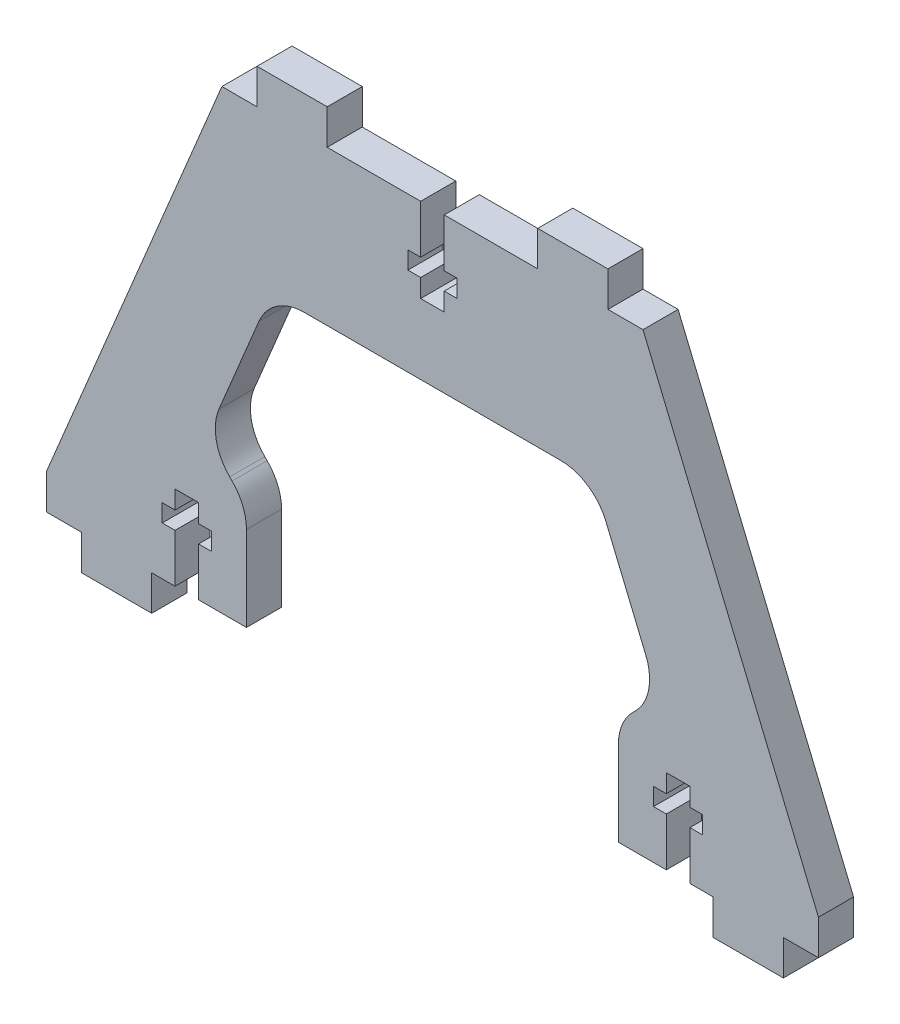
SolidWorks part; units mm, degrees
ref_plane "Front Plane" through (0, 0, 0) normal (0, 0, 1) x (1, 0, 0)
ref_plane "Top Plane" through (0, 0, 0) normal (0, 1, 0) x (1, 0, 0)
ref_plane "Right Plane" through (0, 0, 0) normal (1, 0, 0) x (0, 0, -1)
sketch "Sketch1" plane through (0, 0, 0) normal (0, 0, 1) x (1, 0, 0)
  line L1 (-69.85, 41.275) -> (69.85, 41.275)
  line L2 (-69.85, 41.275) -> (-69.85, -41.275)
  line L3 (-69.85, -41.275) -> (69.85, -41.275)
  line L4 (69.85, 41.275) -> (69.85, -41.275)
  line L5 (-69.85, 41.275) -> (69.85, -41.275) construction
  line L6 (-69.85, -41.275) -> (69.85, 41.275) construction
  point P0 (0, 0)
  dimension "D1" = 82.55
  dimension "D2" = 139.7
extrude "Boss-Extrude1" add sketch "Sketch1" along normal blind 6.35
sketch "Sketch2" plane through (0, 0, 0) normal (0, 0, -1) x (-1, 0, 0)
  line L0 (69.85, -41.275) -> (-69.85, -41.275) construction
  line L1 (-63.5, -41.275) -> (-50.8, -41.275)
  line L2 (-63.5, -41.275) -> (-63.5, -47.625)
  line L3 (-63.5, -47.625) -> (-50.8, -47.625)
  line L4 (-50.8, -41.275) -> (-50.8, -47.625)
  line L5 (-69.85, -41.275) -> (-69.85, 41.275) construction
  line L6 (-69.85, 41.275) -> (69.85, 41.275) construction
  line L7 (-31.75, 41.275) -> (-19.05, 41.275)
  line L8 (-31.75, 41.275) -> (-31.75, 47.625)
  line L9 (-31.75, 47.625) -> (-19.05, 47.625)
  line L10 (-19.05, 41.275) -> (-19.05, 47.625)
  dimension "D1" = 6.35
  dimension "D2" = 12.7
  dimension "D3" = 6.35
  dimension "D4" = 6.35
  dimension "D5" = 12.7
  dimension "D6" = 38.1
extrude "Boss-Extrude2" add sketch "Sketch2" against normal blind 6.35
sketch "Sketch3" plane through (0, 0, 0) normal (0, 0, -1) x (-1, 0, 0)
  line L1 (-46.5836, -41.275) -> (-46.5836, -32.512)
  line L2 (69.85, -41.275) -> (-50.8, -41.275) construction
  line L3 (-46.5836, -32.512) -> (-48.895, -32.512)
  line L4 (-48.895, -32.512) -> (-48.895, -29.337)
  line L5 (-48.895, -29.337) -> (-46.5836, -29.337)
  line L6 (-46.5836, -29.337) -> (-46.5836, -26.035)
  line L7 (-46.5836, -26.035) -> (-42.3164, -26.035)
  line L8 (-44.45, -26.035) -> (-44.45, -41.275) construction
  line L9 (-42.3164, -41.275) -> (-46.5836, -41.275)
  line L10 (-63.5, -47.625) -> (-50.8, -47.625) construction
  line L11 (-42.3164, -29.337) -> (-42.3164, -26.035)
  line L12 (-40.005, -29.337) -> (-42.3164, -29.337)
  line L13 (-40.005, -32.512) -> (-40.005, -29.337)
  line L14 (-42.3164, -32.512) -> (-40.005, -32.512)
  line L15 (-42.3164, -41.275) -> (-42.3164, -32.512)
  line L16 (-50.8, -47.625) -> (-50.8, -41.275) construction
  dimension "D1" = 21.59
  dimension "D2" = 3.302
  dimension "D3" = 3.175
  dimension "D4" = 4.2672
  dimension "D5" = 4.445
  dimension "D6" = 6.35
extrude "Cut-Extrude1" cut sketch "Sketch3" against normal blind 6.35
sketch "Sketch7" plane through (0, 0, 0) normal (0, 0, -1) x (-1, 0, 0)
  line L0 (-38.1, 41.275) -> (-69.85, -34.925)
  line L1 (-69.85, 41.275) -> (-31.75, 41.275) construction
  line L2 (-69.85, -41.275) -> (-69.85, 41.275) construction
  line L3 (-69.85, -34.925) -> (-69.85, 41.275)
  line L4 (-69.85, 41.275) -> (-38.1, 41.275)
  line L5 (-31.75, 47.625) -> (-31.75, 41.275) construction
  dimension "D1" = 6.35
  dimension "D2" = 6.35
extrude "Cut-Extrude8" cut sketch "Sketch7" against normal blind 6.35
mirror "Mirror2" about plane through (0, 0, 0) normal (1, 0, 0) of "Cut-Extrude8", "Boss-Extrude2"
mirror "Mirror4" about plane through (0, 0, 0) normal (1, 0, 0) of "Cut-Extrude1"
sketch "Sketch4" plane through (0, 0, 0) normal (0, 0, -1) x (-1, 0, 0)
  line L0 (0, 41.275) -> (0, 0) construction
  line L2 (2.1336, 41.275) -> (-2.1336, 41.275)
  line L3 (-2.1336, 41.275) -> (-2.1336, 32.512)
  line L4 (-2.1336, 32.512) -> (-4.445, 32.512)
  line L5 (-4.445, 32.512) -> (-4.445, 29.337)
  line L6 (-4.445, 29.337) -> (-2.1336, 29.337)
  line L7 (-2.1336, 29.337) -> (-2.1336, 26.035)
  line L8 (-2.1336, 26.035) -> (2.1336, 26.035)
  line L10 (2.1336, 29.337) -> (2.1336, 26.035)
  line L11 (4.445, 29.337) -> (2.1336, 29.337)
  line L12 (4.445, 32.512) -> (4.445, 29.337)
  line L13 (2.1336, 32.512) -> (4.445, 32.512)
  line L14 (2.1336, 41.275) -> (2.1336, 32.512)
  line L15 (-19.05, 47.625) -> (-31.75, 47.625) construction
  line L16 (-19.05, 41.275) -> (19.05, 41.275) construction
  point P15 (0, 26.035)
  dimension "D1" = 2.1336
  dimension "D2" = 4.445
  dimension "D3" = 21.59
  dimension "D4" = 3.302
  dimension "D5" = 3.175
extrude "Cut-Extrude2" cut sketch "Sketch4" against normal blind 6.35
sketch "Sketch8" plane through (0, 0, 6.35) normal (0, 0, 1) x (1, 0, 0)
  line L0 (-33.655, -22.225) -> (-40.9015, -14.9785)
  line L1 (33.655, -22.225) -> (40.9015, -14.9785)
  line L6 (-69.85, -34.925) -> (-38.1, 41.275) construction
  line L8 (69.85, -34.925) -> (38.1, 41.275) construction
  line L9 (-42.3164, -41.275) -> (42.3164, -41.275) construction
  line L10 (-69.85, -34.925) -> (-38.1, 41.275) construction
  line L11 (-33.655, -22.225) -> (-33.655, -41.275)
  line L12 (69.85, -34.925) -> (38.1, 41.275) construction
  line L13 (-33.655, -41.275) -> (33.655, -41.275)
  line L14 (-40.9015, -14.9785) -> (-29.1042, 13.335)
  line L15 (-29.1042, 13.335) -> (29.1042, 13.335)
  line L16 (2.1336, 26.035) -> (-2.1336, 26.035) construction
  line L17 (-52.2654, -42.2519) -> (-20.5154, 33.9481) construction
  line L18 (52.2654, -42.2519) -> (20.5154, 33.9481) construction
  line L19 (33.655, -22.225) -> (33.655, -41.275)
  line L20 (40.9015, -14.9785) -> (29.1042, 13.335)
  line L22 (40.005, -32.512) -> (40.005, -29.337) construction
  line L23 (-40.005, -32.512) -> (-40.005, -29.337) construction
  point P16 (40.005, -30.9245)
  dimension "D3" = 12.7
  dimension "D4" = 6.35
  dimension "D5" = 6.35
  dimension "D8" = 19.05
  dimension "D9" = 225
  dimension "D1" = 19.05
  dimension "D2" = 19.05
extrude "Cut-Extrude9" cut sketch "Sketch8" against normal through all and the other way through all
fillet "Fillet1" radius 8.89 6 edges at (33.655, -22.225, 3.175) (40.9015, -14.9785, 3.175) (29.1042, 13.335, 3.175) (-29.1042, 13.335, 3.175) (-40.9015, -14.9785, 3.175) (-33.655, -22.225, 3.175)
